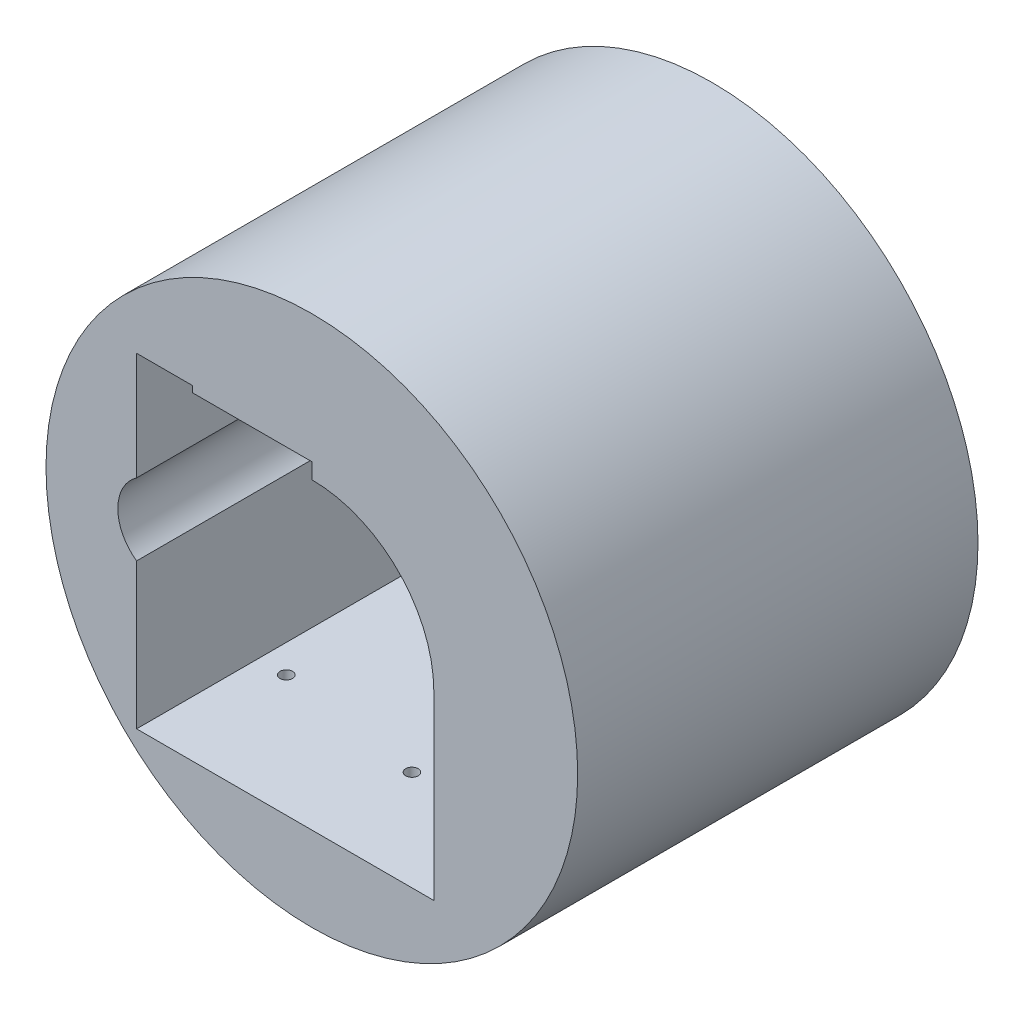
SolidWorks part; units mm, degrees
ref_plane "Front Plane" through (0, 0, 0) normal (0, 0, 1) x (1, 0, 0)
ref_plane "Top Plane" through (0, 0, 0) normal (0, 1, 0) x (1, 0, 0)
ref_plane "Right Plane" through (0, 0, 0) normal (1, 0, 0) x (0, 0, -1)
sketch "Sketch1" plane through (0, 0, -49.1287) normal (0, 0, -1) x (-1, 0, 0)
  line L0 (-13.8011, 15.8348) -> (-13.8011, -4)
  line L1 (-13.8011, 19.2554) -> (-13.8011, -4) construction
  line L2 (-13.8011, -4) -> (-61.3161, -4)
  line L3 (-61.3161, -4) -> (-61.3161, 25)
  line L4 (-13.8011, 34.1652) -> (-13.8011, 47)
  line L5 (-41.8161, 44.5) -> (-41.8161, 47)
  line L6 (-41.8161, 47) -> (-13.8011, 47)
  line L7 (-13.8011, 34.1652) -> (-13.8011, 30.7446)
  line L8 (-13.8011, 28) -> (-13.8011, 40.4952) construction
  line L9 (-13.8011, 15.8348) -> (-13.8011, 19.2554)
  arc A0 (-44.7791, 25.4702) -> (-42.5352, 27.9126) centre (-41.8161, 25) ccw construction
  arc A1 (-44.7791, 25.4702) -> (-42.5352, 27.9126) centre (-41.8161, 25) ccw construction
  circle A2 centre (-41.8161, 25) radius 42.5
  circle A3 centre (-17.8011, 25) radius 10 construction
  arc A4 (-22.9119, 29.7833) -> (-61.3161, 25) centre (-41.8161, 25) ccw construction
  arc A5 (-41.8161, 44.5) -> (-61.3161, 25) centre (-41.8161, 25) ccw
  arc A9 (-13.8011, 19.2554) -> (-13.8011, 30.7446) centre (-17.8011, 25) ccw
  dimension "D1" = 85
extrude "Boss-Extrude1" add sketch "Sketch1" against normal blind 64
ref_plane "Plane1" through (0, -17.5, 0) normal (0, -1, 0) x (-1, 0, 0)
sketch "Sketch2" plane through (0, -17.5, 0) normal (0, -1, 0) x (-1, 0, 0)
  circle A0 centre (-18.3011, 4.5578) radius 1 construction
  circle A1 centre (-18.3011, 32.5578) radius 1 construction
  circle A2 centre (-18.3011, 4.5578) radius 1
  circle A3 centre (-18.3011, 32.5578) radius 1
  circle A6 centre (-41.8161, 1.1287) radius 1 construction
  circle A7 centre (-41.8161, 1.1287) radius 1
extrude "Cut-Extrude1" cut sketch "Sketch2" against normal up to surface (13.5 mm away) up to face at (37.5586, -4, -17.1287)
sketch "Sketch3" plane through (0, -17.5, 0) normal (0, -1, 0) x (-1, 0, 0)
  circle A0 centre (-41.8161, 1.1287) radius 2.25
  circle A1 centre (-18.3011, 4.5578) radius 2.25
  circle A2 centre (-18.3011, 32.5578) radius 2.25
  dimension "D1" = 4.5
extrude "Cut-Extrude2" cut sketch "Sketch3" against normal blind 5
sketch "Sketch4" plane through (0, -17.5, 0) normal (0, -1, 0) x (-1, 0, 0)
  circle A0 centre (-18.3011, 4.5578) radius 2.25
  circle A1 centre (-18.3011, 32.5578) radius 2.25
extrude "Cut-Extrude3" cut sketch "Sketch4" against normal blind 12
sketch "Sketch5" plane through (0, 0, -49.1287) normal (0, 0, -1) x (-1, 0, 0)
  line L0 (-21.8011, 47) -> (-13.8011, 47)
  line L1 (-13.8011, 47) -> (-13.8011, 48)
  line L7 (-13.8011, 48) -> (-21.8011, 48)
  line L17 (-21.8011, 47) -> (-22.7487, 47)
  line L19 (-21.8011, 48) -> (-22.7487, 48)
  line L20 (-22.7487, 47) -> (-22.7487, 48)
extrude "Cut-Extrude4" cut sketch "Sketch5" against normal through all
